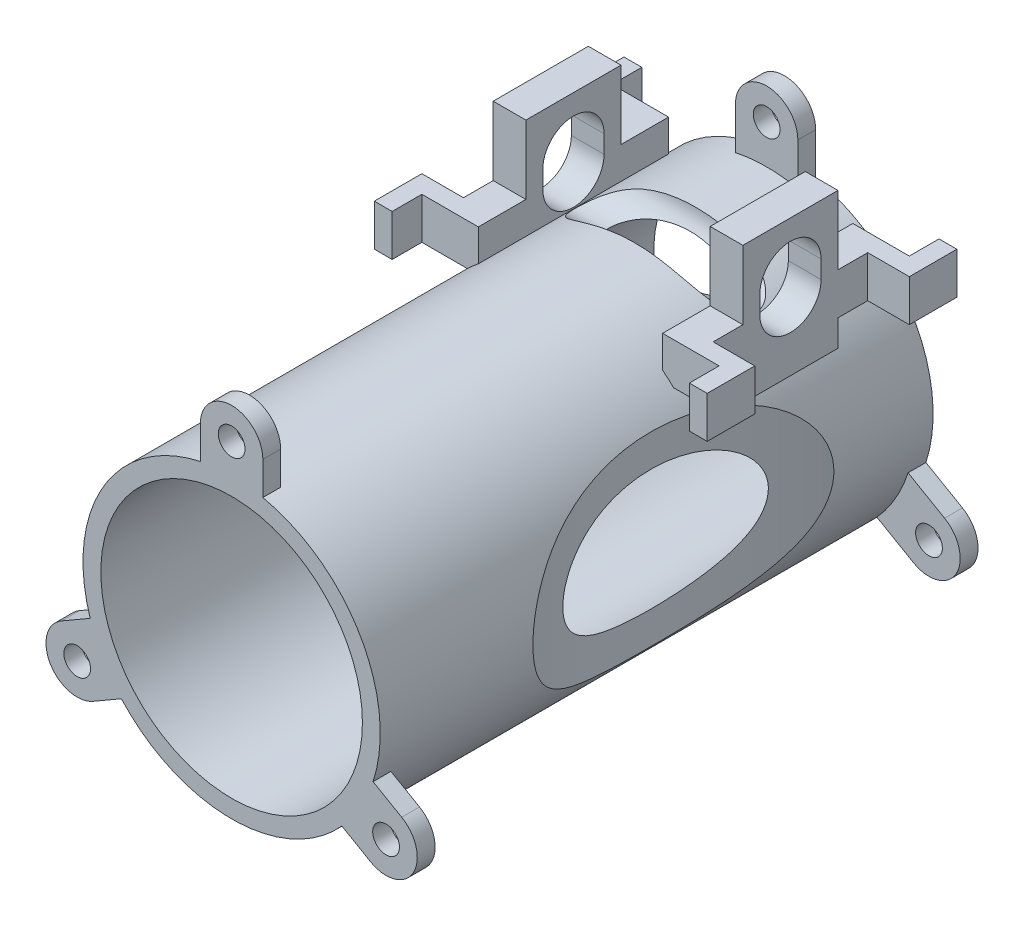
SolidWorks part; units mm, degrees
ref_plane "Front Plane" through (0, 0, 0) normal (0, 0, 1) x (1, 0, 0)
ref_plane "Top Plane" through (0, 0, 0) normal (0, 1, 0) x (1, 0, 0)
ref_plane "Right Plane" through (0, 0, 0) normal (1, 0, 0) x (0, 0, -1)
sketch "Sketch1" plane through (0, 0, 0) normal (0, 0, 1) x (1, 0, 0)
  circle A0 centre (0, 0) radius 22
  circle A1 centre (0, 0) radius 25
  dimension "D1" = 44
  dimension "D2" = 3
extrude "Boss-Extrude1" add sketch "Sketch1" along normal blind 40
ref_plane "Plane1" through (0, 0, 20) normal (0, 0, 1) x (1, 0, 0)
sketch "Sketch3" plane through (0, 0, 0) normal (1, 0, 0) x (0, 0, -1)
  line L0 (0, 25) -> (-40, 25) construction
  circle A0 centre (-20, 25) radius 5.15
  dimension "D1" = 10.3
extrude "Cut-Extrude1" cut sketch "Sketch3" against normal mid plane 50
sketch "Sketch7" plane through (0, 0, 40) normal (0, 0, 1) x (1, 0, 0)
  circle A0 centre (0, 0) radius 22
  circle A1 centre (0, 0) radius 25
extrude "Boss-Extrude4" add sketch "Sketch7" along normal blind 53
ref_plane "Plane2" through (-25, 0, 0) normal (-1, 0, 0) x (0, 0, 1)
sketch "Sketch9" plane through (0, 0, 0) normal (0, 0, -1) x (-1, 0, 0)
  line L0 (0, 0) -> (0, 31.533) construction
  line L1 (-5.25, 31.533) -> (-5.25, 24.4425)
  line L2 (5.25, 31.533) -> (5.25, 24.4425)
  circle A0 centre (0, 31.533) radius 2.25
  circle A1 centre (0, 31.533) radius 5.25
  circle A2 centre (0, 0) radius 25 construction
  arc A3 (-5.25, 24.4425) -> (5.25, 24.4425) centre (0, 0) cw
  circle A6 centre (0, 31.533) radius 2 construction
  dimension "D1" = 4.5
  dimension "D2" = 3
extrude "Boss-Extrude5" add sketch "Sketch9" against normal blind 3
pattern_circular "CirPattern1" count 3 over 360 about axis through (0, 0, 0) along (0, 0, 1) of "Boss-Extrude5"
sketch "Sketch10" plane through (0, 0, 93) normal (0, 0, 1) x (1, 0, 0)
  line L0 (-5.25, 30) -> (-5.25, 24.4425)
  line L1 (5.25, 30) -> (5.25, 24.4425)
  line L2 (0, 0) -> (0, 30) construction
  circle A0 centre (0, 30) radius 2.25
  circle A1 centre (0, 30) radius 5.25
  arc A2 (-5.25, 24.4425) -> (5.25, 24.4425) centre (0, 0) cw
  circle A3 centre (0, 0) radius 25 construction
  circle M5 centre (0, 0) radius 25
  dimension "D2" = 4.5
  dimension "D3" = 30
  dimension "D1" = 3
extrude "Boss-Extrude6" add sketch "Sketch10" against normal blind 3 contours A1 A0 M5 | A1 L0 M5 | A1 L1 M5
pattern_circular "CirPattern2" count 3 every 120 about axis through (0, 0, 0) along (0, 0, 1) of "Boss-Extrude6"
ref_plane "Plane3" through (0, 11.51, 0) normal (0, 1, 0) x (1, 0, 0)
sketch "Sketch14" plane through (0, 0, 20) normal (0, 0, 1) x (1, 0, 0)
  line L0 (-21, 13.5647) -> (-21, 36.5647)
  line L1 (-21, 36.5647) -> (-15.5, 36.5647)
  line L2 (-15.5, 36.5647) -> (-15.5, 19.615)
  line L3 (-25, 27.5) -> (-25, -27.5) construction
  arc A0 (-5.25, 24.4425) -> (-23.7929, -7.6746) centre (0, 0) ccw construction
  arc A1 (-15.5, 19.615) -> (-21, 13.5647) centre (0, 0) ccw
  dimension "D1" = 23
  dimension "D2" = 4
  dimension "D3" = 5.5
extrude "Boss-Extrude7" add sketch "Sketch14" along normal mid plane 16
sketch "Sketch15" plane through (-21, 0, 0) normal (-1, 0, 0) x (0, 0, 1)
  line L0 (20, 25) -> (20, 28) construction
  line L1 (20, -27.5) -> (20, 27.5) construction
  line L2 (14.85, 25) -> (14.85, 28)
  line L3 (25.15, 25) -> (25.15, 28)
  line L4 (90, 25) -> (25.15, 25) construction
  arc A0 (14.85, 25) -> (25.15, 25) centre (20, 25) ccw
  arc A1 (25.15, 28) -> (14.85, 28) centre (20, 28) ccw
  point P4 (20, 26.5)
  dimension "D1" = 5.15
  dimension "D2" = 3
extrude "Cut-Extrude5" cut sketch "Sketch15" against normal blind 16
ref_plane "Plane5" through (0, 25, 0) normal (0, 1, 0) x (1, 0, 0)
sketch "Sketch17" plane through (0, 25, 0) normal (0, 1, 0) x (1, 0, 0)
  line L1 (-15.5, -28) -> (-21, -28)
  line L2 (-15.5, -28) -> (-15.5, -33)
  line L3 (-15.5, -33) -> (-21, -33)
  line L4 (-21, -28) -> (-21, -33)
  line L5 (-15.5, -28) -> (-21, -33) construction
  line L6 (-15.5, -33) -> (-21, -28) construction
  line L7 (-15.5, -33) -> (-28, -33)
  line L8 (-15.5, -33) -> (-15.5, -36)
  line L9 (-15.5, -36) -> (-28, -36)
  line L10 (-28, -33) -> (-28, -36)
  line L11 (-15.5, -33) -> (-28, -36) construction
  line L12 (-15.5, -36) -> (-28, -33) construction
  line L13 (-28, -36) -> (-25, -36)
  line L14 (-28, -36) -> (-28, -41)
  line L15 (-28, -41) -> (-25, -41)
  line L16 (-25, -36) -> (-25, -41)
  line L17 (-28, -36) -> (-25, -41) construction
  line L18 (-28, -41) -> (-25, -36) construction
  point P4 (-18.25, -30.5)
  point P10 (-21.75, -34.5)
  point P14 (-26.5, -38.5)
  dimension "D1" = 5
  dimension "D2" = 3
  dimension "D3" = 5
  dimension "D4" = 4
extrude "Boss-Extrude8" add sketch "Sketch17" against normal blind 7 contours L16 L9 L14 L15 | L7 L10 L9 L8 L3 | L1 L4 L3 L2
mirror "Mirror1" about plane through (0, 0, 20) normal (0, 0, 1) of "Boss-Extrude8"
mirror "Mirror2" about plane through (0, 0, 0) normal (1, 0, 0) of "Mirror1", "Boss-Extrude8", "Cut-Extrude5", "Boss-Extrude7"
sketch "Sketch12" plane through (0, 11.51, 0) normal (0, 1, 0) x (1, 0, 0)
  line L0 (0, -44.5194) -> (0, -33.7673) construction
  line L1 (-24.6834, 0) -> (-32.5584, 0) construction
  circle A0 centre (-80.5, -42) radius 60
  circle A1 centre (80.5, -42) radius 60
  circle A2 centre (-80.5, -42) radius 61
  circle A3 centre (80.5, -42) radius 61
  dimension "D1" = 120
  dimension "D2" = 161
  dimension "D3" = 42
  dimension "D4" = 1
extrude "Cut-Extrude4" cut sketch "Sketch12" against normal blind 41 and the other way blind 6 contours A2 A0 | A1 | A3 A1
